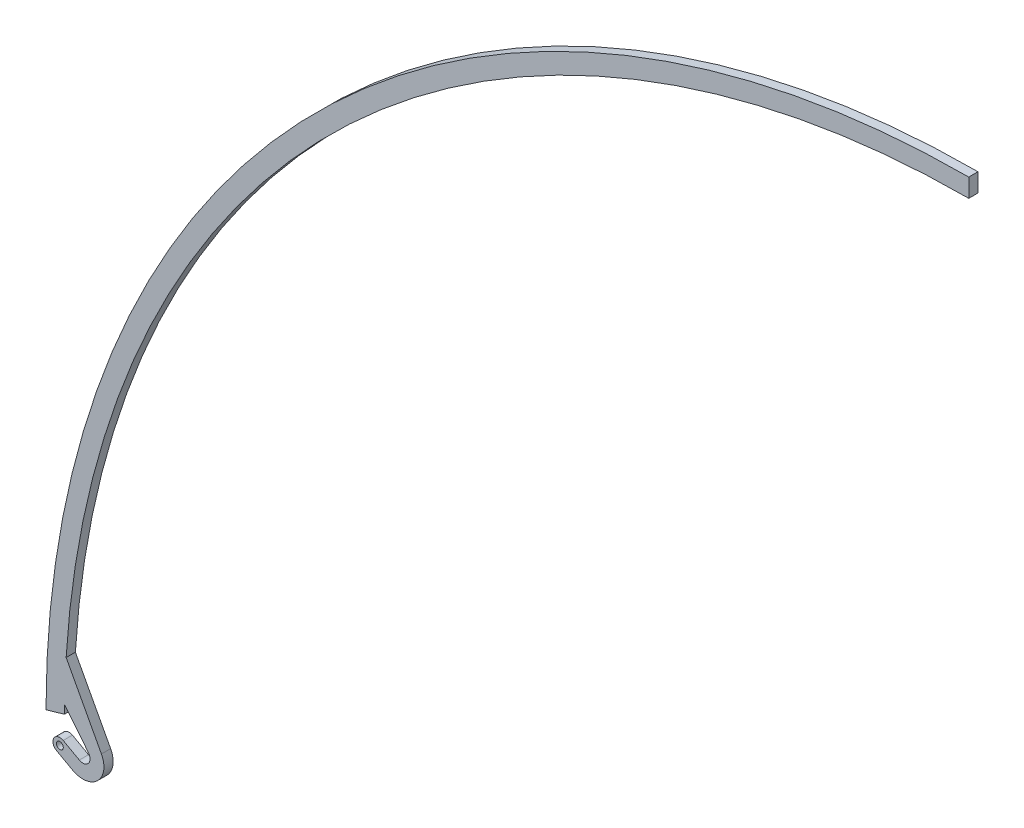
SolidWorks part; units mm, degrees
ref_plane "Front Plane" through (0, 0, 0) normal (0, 0, 1) x (1, 0, 0)
ref_plane "Top Plane" through (0, 0, 0) normal (0, 1, 0) x (1, 0, 0)
ref_plane "Right Plane" through (0, 0, 0) normal (1, 0, 0) x (0, 0, -1)
sketch "Sketch5" plane through (0, 0, 0) normal (0, 0, 1) x (1, 0, 0)
  line L0 (1000, 980) -> (1000, 1000)
  line L1 (0, -1) -> (0, -26) construction
  line L2 (0, -1) -> (5, -1) construction
  line L3 (44.1364, -24.9646) -> (22.2558, -12.8717) construction
  line L4 (22.2558, -12.8717) -> (15, -26) construction
  line L5 (44.1364, -24.9646) -> (41.7178, -29.3408) construction
  line L6 (41.7178, -29.3408) -> (19.8372, -17.2478) construction
  line L7 (18.6279, -19.4358) -> (36.0925, -29.0882)
  line L8 (15, -26) -> (0, -26) construction
  line L9 (5, -1) -> (5, -26) construction
  line L10 (0, 0) -> (20.0173, 5.8224)
  line L11 (41.7178, -29.3408) -> (41.8414, -29.8252) construction
  line L12 (46.0294, -17.2821) -> (20.1148, 15)
  line L13 (11.3721, -32.5642) -> (28.8367, -42.2166)
  line L14 (62.7609, -12.2155) -> (62.7609, -45.0695) construction
  line L15 (482.6231, -267.3083) -> (1151.6211, 943.1498) construction
  line L16 (22.2558, -12.8717) -> (-0.2419, -0.4376) construction
  line L17 (-0.2419, -0.4376) -> (0, 0) construction
  line L18 (60.056, -11.4174) -> (21.8385, 60)
  line L19 (37.7355, -7.749) -> (38.1254, -7.436) construction
  line L20 (-611.4056, 337.3415) -> (63.1113, 1557.785) construction
  line L21 (62.7609, -45.0695) -> (0, -45.0695) construction
  arc A0 (0, 0) -> (1000, 1000) centre (1000, 0) cw
  arc A1 (20.0173, 5.8224) -> (20.1148, 15) centre (1000, 0) cw
  arc A2 (0, -1) -> (44.1364, -24.9646) centre (15, -26) cw construction
  arc A3 (18.6279, -19.4358) -> (11.3721, -32.5642) centre (15, -26) ccw
  arc A4 (36.0925, -29.0882) -> (46.0294, -17.2821) centre (39.8966, -22.2052) ccw
  arc A5 (21.8385, 60) -> (1000, 980) centre (1000, 0) cw
  arc A6 (28.8367, -42.2166) -> (60.056, -11.4174) centre (39.8966, -22.2052) ccw
  circle A7 centre (15, -26) radius 3.75
  point P8 (15, -26)
  dimension "D2" = 1000
  dimension "D1" = 980
  dimension "D8" = 7.5
  dimension "D11" = 15
  dimension "D12" = 60
  dimension "D15" = 7.5
  dimension "D3" = 1
  dimension "D4" = 25
  dimension "D5" = 15
  dimension "D6" = 0.5
  dimension "D7" = 5
  dimension "D9" = 0.5
  dimension "D10" = 0.5
  dimension "D13" = 501
  dimension "D14" = 62.7609
  dimension "D16" = 118.929
  dimension "D17" = 749
  dimension "D18" = 44.0695
extrude "Boss-Extrude1" add sketch "Sketch5" along normal mid plane 10
